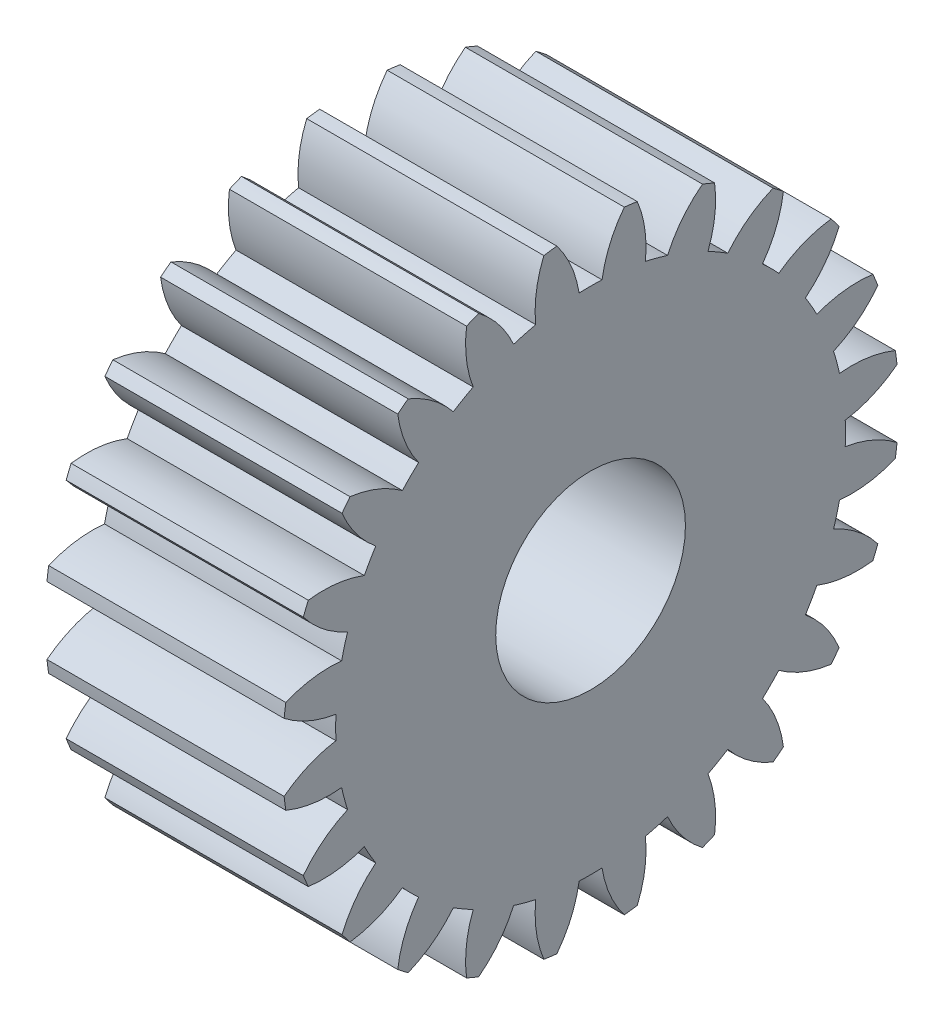
SolidWorks part; units mm, degrees
ref_plane "Plane1" through (0, 0, 0) normal (0, 0, 1) x (1, 0, 0)
ref_plane "Plane2" through (0, 0, 0) normal (0, 1, 0) x (1, 0, 0)
ref_plane "Plane3" through (0, 0, 0) normal (1, 0, 0) x (0, 0, -1)
sketch "HoldingSke" plane through (0, 0, 0) normal (0, 1, 0) x (1, 0, 0)
  line L0 (0, 0) -> (1.8271, -0.8135)
  line L1 (-15, 0) -> (100, 0) construction
  line L2 (0, 0) -> (-2.1039, 2.3779)
  line L3 (0, 0) -> (-11.863, 4.5341)
  line L4 (0, 0) -> (7.8894, 3.5126)
  line L5 (0, 0) -> (-46.8476, -17.4728)
  line L6 (0, 0) -> (-4.1448, -2.7965)
  line L7 (-2.1039, 2.3779) -> (8.6586, 51.2059)
  line L8 (-76.2, 54.61) -> (-75.5, 54.61)
  line L9 (-71.009, 38.7566) -> (-53.1078, 45.2721)
  line L10 (-76.2, 71.12) -> (104.1128, 71.12)
  line L11 (0, 0) -> (-5, 0)
  line L12 (-76.2, 101.6) -> (-76.181, 101.6)
  line L13 (24.9733, 27.94) -> (52.9518, 28.4284)
  line L14 (24.9733, 27.94) -> (24.9743, 27.94)
  line L15 (24.9733, 27.94) -> (100.4006, 29.5858)
  line L16 (-63.627, -0.5) -> (-12.827, -0.5)
  circle A0 centre (0, 0) radius 2
  circle A1 centre (0, 0) radius 5.374
  circle A2 centre (0, 0) radius 37.5
  circle A3 centre (0, 0) radius 2
  dimension "MHD" = 10.748
  dimension "Hub_dia" = 75
  dimension "Bore" = 4
  dimension "MBD" = 4
  dimension "Num_teeth" = 24
  dimension "Pitch" = 2
  dimension "Overall_len" = 50
  dimension "Show_teeth" = 24
  dimension "Thickness" = 5
  dimension "OAL" = 50.0001
  dimension "T_dim" = 0.7
  dimension "Ap" = 20
  dimension "H" = 19.05
  dimension "Pitch_radius" = 180.3128
  dimension "Width" = 5
  dimension "Backlash" = 0.019
  dimension "Addendum_fac" = 1
  dimension "Dedendum_fac" = 1.25
  dimension "Clearance_fac" = 0.25
  dimension "Dedendum_add" = 0.001
  dimension "Module" = 0.5
sketch "BasProSke" plane through (0, 0, 0) normal (0, 1, 0) x (1, 0, 0)
  line L0 (-10, 0) -> (60, 0) construction
  line L1 (0, 0) -> (0, 6.5)
  line L2 (0, 0) -> (5, 0)
  line L3 (5, 0) -> (5, 6.5)
  line L4 (5, 6.5) -> (0, 6.5)
  dimension "Thickness" = 5
  dimension "Diameter" = 13
revolve "Base-Revolve" add sketch "BasProSke" angle 360 about L0
sketch "TooCutSke" plane through (0, 0, 0) normal (1, 0, 0) x (0, 0, -1)
  line L1 (0, 0) -> (0, 107) construction
  line L2 (0, 0) -> (-0.4257, 5.9849) construction
  line L3 (0, 0) -> (-1.5635, 11.876) construction
  line L4 (-0.4257, 5.9849) -> (-0.7818, 5.938) construction
  arc A0 (0.2416, 5.3686) -> (-0.2416, 5.3686) centre (0, 0) ccw
  arc A1 (0.7297, 6.4845) -> (-0.7297, 6.4845) centre (0, 0) ccw
  circle A2 centre (0, 0) radius 6 construction
  circle A3 centre (0, 0) radius 5.6382 construction
  arc A4 (-0.2416, 5.3686) -> (-0.7297, 6.4845) centre (-2.6126, 4.9963) ccw
  arc A5 (0.7297, 6.4845) -> (0.2416, 5.3686) centre (2.6126, 4.9963) ccw
  dimension "Root_dia" = 10.748
  dimension "Overcut_dia" = 13.0508
  dimension "Pitch_dia" = 12
  dimension "Base_dia" = 11.2763
  dimension "Flank_rad" = 2.4
  dimension "Half_ang" = 7.5
  dimension "Half_CT" = 0.3592
extrude "ToothCut" cut sketch "TooCutSke" along normal through all
fillet "Breaks" [suppressed] radius 0.01
fillet "RootFillets" [suppressed] radius 0.126
pattern_circular "TeethCuts" count 24 every 15 about axis through (-10, 0, 0) along (1, 0, 0) of "ToothCut", "RootFillets", "Breaks"
sketch "HubNeaOneSke" plane through (0, 0, 0) normal (-1, 0, 0) x (0, 0, 1)
  circle A0 centre (0, 0) radius 5.374
  dimension "Diameter" = 10.748
extrude "HubNearOne" [suppressed] add sketch "HubNeaOneSke" along normal blind 45.0001
sketch "HubNeaBotSke" plane through (0, 0, 0) normal (-1, 0, 0) x (0, 0, 1)
  circle A0 centre (0, 0) radius 5.374
  dimension "Diameter" = 10.748
extrude "HubNearBoth" [suppressed] add sketch "HubNeaBotSke" along normal blind 22.5
ref_plane "FarPln" through (5, 0, 0) normal (1, 0, 0) x (0, 0, -1)
sketch "HubFarSke" plane through (5, 0, 0) normal (1, 0, 0) x (0, 0, -1)
  circle A0 centre (0, 0) radius 5.374
  dimension "Diameter" = 10.748
extrude "HubFar" [suppressed] add sketch "HubFarSke" along normal blind 22.5
sketch "BorSke" plane through (0, 0, 0) normal (1, 0, 0) x (0, 0, -1)
  circle A0 centre (0, 0) radius 2
  dimension "Diameter" = 4
extrude "Bore" cut sketch "BorSke" along normal mid plane 100.0001
sketch "KeySke" plane through (0, 0, 0) normal (1, 0, 0) x (0, 0, -1)
  line L0 (-0.8, 0) -> (-0.8, 2.7)
  line L1 (-0.8, 2.7) -> (0.8, 2.7)
  line L2 (0.8, 2.7) -> (0.8, 0)
  line L3 (0, 0) -> (0, 34) construction
  line L4 (-0.8, 0) -> (0.8, 0)
  dimension "Offset" = 2.7
  dimension "Width" = 1.6
extrude "Keyway" [suppressed] cut sketch "KeySke" along normal mid plane 100.0001
pattern_circular "Keyway2" [suppressed] count 2 every 90 about axis through (-10, 0, 0) along (1, 0, 0)
equation "' \"Module@HoldingSke\" = 6.35"
equation "' \"Num_teeth@HoldingSke\" = 12"
equation "' \"Ap@HoldingSke\" =  20"
equation "' \"Ap@HoldingSke\" = 20"
equation "' \"Width@HoldingSke\" = 0.5 * 25.4"
equation "' \"Hub_dia@HoldingSke\"= 1 * 25.4"
equation "' \"Hub_dia@HoldingSke\" = 1 * 25.4"
equation "' \"Overall_len@HoldingSke\" = 1.0 * 25.4"
equation "' \"Bore@HoldingSke\" = 0.75 * 25.4"
equation "' \"T_dim@HoldingSke\" = 0.1 * 25.4"
equation "' \"Width@KeySke\" = 0.25 * 25.4"
equation "' \"Show_teeth@HoldingSke\" = 13"
equation "' \"Backlash@HoldingSke\" = 0.009 * 25.4"
equation "' \"Addendum_fac@HoldingSke\" = 1.0"
equation "' \"Dedendum_fac@HoldingSke\" = 1.25"
equation "' \"Dedendum_add@HoldingSke\" = 0.00005 * 25.4"
equation "' \"Clearance_fac@HoldingSke\" = 0.25"
equation "\"Pitch@HoldingSke\" = 1 / \"Module@HoldingSke\""
equation "\"Overcut_dia@TooCutSke\" = (\"Num_teeth@HoldingSke\" + 2 * \"Addendum_fac@HoldingSke\") / \"Pitch@HoldingSke\" + 0.002 * 25.4"
equation "\"Pitch_dia@TooCutSke\" = \"Num_teeth@HoldingSke\" / \"Pitch@HoldingSke\""
equation "\"Base_dia@TooCutSke\" = \"Num_teeth@HoldingSke\" / \"Pitch@HoldingSke\" * cos((\"Ap@HoldingSke\"  * 3.14159265 / 180))"
equation "\"Root_dia@TooCutSke\" = (\"Num_teeth@HoldingSke\" + 2) / \"Pitch@HoldingSke\" - 2 * (\"Addendum_fac@HoldingSke\" + \"Dedendum_fac@HoldingSke\") / \"Pitch@HoldingSke\" - \"Dedendum_add@HoldingSke\" * 2"
equation "\"Half_ang@TooCutSke\" = 180 / \"Num_teeth@HoldingSke\""
equation "\"Half_CT@TooCutSke\" = \"Num_teeth@HoldingSke\" / \"Pitch@HoldingSke\" * sin((3.14159265 / 2 / \"Num_teeth@HoldingSke\")) / 2 - 7 * \"Backlash@HoldingSke\" / 4"
equation "\"Flank_rad@TooCutSke\" = \"Num_teeth@HoldingSke\" / \"Pitch@HoldingSke\" / 5"
equation "\"Radius@RootFillets\" = \"Clearance_fac@HoldingSke\" / \"Pitch@HoldingSke\" + \"Dedendum_add@HoldingSke\""
equation "\"Break_rad@Breaks\" = 0.02 / \"Pitch@HoldingSke\""
equation "\"Thickness@HoldingSke\" = \"Width@HoldingSke\""
equation "\"OAL@HoldingSke\" = \"Thickness@HoldingSke\""
equation "\"MHD@HoldingSke\" = (\"Num_teeth@HoldingSke\" + 2) / \"Pitch@HoldingSke\" - 2 * (\"Addendum_fac@HoldingSke\" + \"Dedendum_fac@HoldingSke\")  / \"Pitch@HoldingSke\" - \"Dedendum_add@HoldingSke\" * 2"
equation "\"MBD@HoldingSke\" = (\"Num_teeth@HoldingSke\" + 2) / \"Pitch@HoldingSke\" - 2 * (\"Addendum_fac@HoldingSke\" + \"Dedendum_fac@HoldingSke\")  / \"Pitch@HoldingSke\" - \"Dedendum_add@HoldingSke\" * 2 - 0.002 * 25.4"
equation "\"MHD@HoldingSke\" = ((sgn( \"MHD@HoldingSke\" - \"Hub_dia@HoldingSke\" )-1)*( \"MHD@HoldingSke\" - \"Hub_dia@HoldingSke\" ))/-2+ \"Hub_dia@HoldingSke\""
equation "\"MBD@HoldingSke\" = ((sgn( \"MBD@HoldingSke\" - \"Bore@HoldingSke\" )-1)*( \"MBD@HoldingSke\" - \"Bore@HoldingSke\" ))/-2+ \"Bore@HoldingSke\""
equation "\"OAL@HoldingSke\" = ((sgn( \"OAL@HoldingSke\" - \"Overall_len@HoldingSke\" )+1)*( \"OAL@HoldingSke\" - \"Overall_len@HoldingSke\" ))/2 + \"Overall_len@HoldingSke\" + 0.000002 * 25.4"
equation "\"Num_teeth@TeethCuts\" = int( \"Show_teeth@HoldingSke\" ) + 1"
equation "\"Num_teeth@TeethCuts\" = ((sgn( \"Num_teeth@TeethCuts\" - \"Num_teeth@HoldingSke\" )-1)*( \"Num_teeth@TeethCuts\" - \"Num_teeth@HoldingSke\" ))/-2+ \"Num_teeth@HoldingSke\""
equation "\"Num_teeth@TeethCuts\" = ((sgn( \"Num_teeth@TeethCuts\" - 2.0)+1)*( \"Num_teeth@TeethCuts\" - 2.0))/2 +2.0"
equation "\"Angle@TeethCuts\" = 360.0 / \"Num_teeth@HoldingSke\""
equation "\"Diameter@BasProSke\" = (\"Num_teeth@HoldingSke\" + 2 * \"Addendum_fac@HoldingSke\") / \"Pitch@HoldingSke\""
equation "\"Thickness@BasProSke\"  = \"Thickness@HoldingSke\""
equation "' \"Fillet_rad@BasProSke\" =  \"Thickness@HoldingSke\" * 0.05"
equation "' \"Fillet_rad@BasProSke\" = \"Thickness@HoldingSke\" * 0.05"
equation "\"MHD@HoldingSke\" = ((sgn( \"MHD@HoldingSke\" - \"Root_dia@TooCutSke\" )-1)*( \"MHD@HoldingSke\" - \"Root_dia@TooCutSke\" ))/-2+ \"Root_dia@TooCutSke\""
equation "\"Diameter@HubNeaOneSke\" = \"MHD@HoldingSke\""
equation "\"Length@HubNearOne\" = \"OAL@HoldingSke\" - \"Thickness@BasProSke\""
equation "\"Diameter@HubNeaBotSke\" = \"MHD@HoldingSke\""
equation "\"Length@HubNearBoth\" = ( \"OAL@HoldingSke\" - \"Thickness@BasProSke\" ) / 2.0"
equation "\"Thickness@FarPln\" = \"Thickness@BasProSke\""
equation "\"Diameter@HubFarSke\" = \"MHD@HoldingSke\""
equation "\"Length@HubFar\" = ( \"OAL@HoldingSke\" - \"Thickness@BasProSke\" ) / 2.0"
equation "\"Diameter@BorSke\" = \"MBD@HoldingSke\""
equation "\"D1@Bore\" = \"OAL@HoldingSke\" * 2.0"
equation "\"D1@Keyway\" = \"OAL@HoldingSke\" * 2.0"
equation "\"Offset@KeySke\" = \"T_dim@HoldingSke\" + \"MBD@HoldingSke\" / 2.0"
